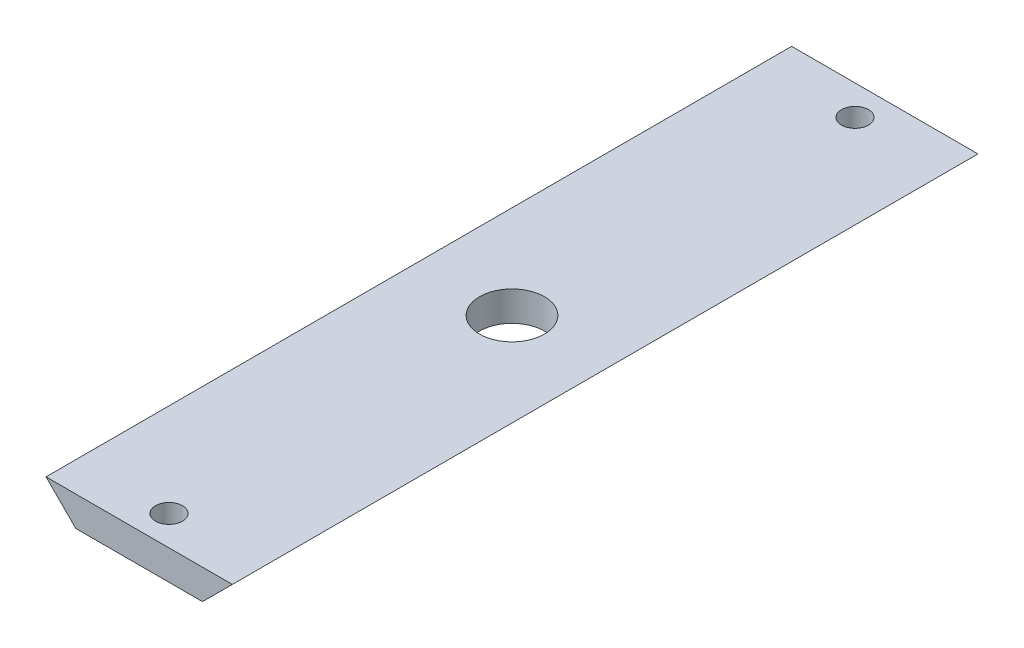
SolidWorks part; units mm, degrees
material "6061-T6 (SS)"
ref_plane "Front" through (0, 0, 0) normal (0, 0, 1) x (1, 0, 0)
ref_plane "Top" through (0, 0, 0) normal (0, 1, 0) x (1, 0, 0)
ref_plane "Right" through (0, 0, 0) normal (1, 0, 0) x (0, 0, -1)
sketch "Sketch1" plane through (0, 0, 0) normal (0, 0, 1) x (1, 0, 0)
  line L0 (0, 0) -> (9.9187, 0)
  line L1 (9.9187, 0) -> (6.7437, -3.175)
  line L2 (6.7437, -3.175) -> (0, -3.175)
  line L3 (0, -3.175) -> (0, 0)
  line L4 (0, 0) -> (0, 17.7372) construction
  dimension "D1" = 13.4874
  dimension "D2" = 45
  dimension "D3" = 3.175
extrude "Boss-Extrude1" add sketch "Sketch1" along normal blind 39.6875
mirror "Mirror1" about plane through (0, -3.175, 39.6875) normal (1, 0, 0) of bodies 101
sketch "Sketch2" plane through (0, 0, 0) normal (0, 1, 0) x (1, 0, 0)
  line L0 (0, 0) -> (0, -36.5125) construction
  line L1 (9.9187, -39.6875) -> (-9.9187, -39.6875) construction
  circle A0 centre (0, -36.5125) radius 1.4351
  dimension "D1" = 2.8702
  dimension "D2" = 3.175
extrude "Cut-Extrude1" cut sketch "Sketch2" against normal through all
mirror "Mirror2" about plane through (0, 0, 0) normal (0, 0, -1) of bodies 103
hole_wizard "5/16-24 Tapped Hole1" positions "Sketch4" profile "Sketch3" tap size "5/16-24" standard "Ansi Inch" end condition through all
sketch "Sketch4" plane through (0, 0, 0) normal (0, 1, 0) x (-1, 0, 0)
  point P1 (0, 0)
sketch "Sketch3" plane through (0, 0, 0) normal (1, 0, 0) x (0, 0, 1)
  line L0 (0, 0) -> (0, 3.175)
  line L1 (0, 3.175) -> (3.4544, 3.175)
  line L2 (3.4544, 3.175) -> (3.4544, 0)
  line L5 (3.4544, 0) -> (0, 0)
  line L11 (0, -6.35) -> (0, 107.95) construction
  dimension "Thru Tap Drill Dia." = 6.9088
  dimension "Thru Tap Drill Depth" = 3.175
cosmetic thread "Hole Thread1" parameters "D2"=7.9375
